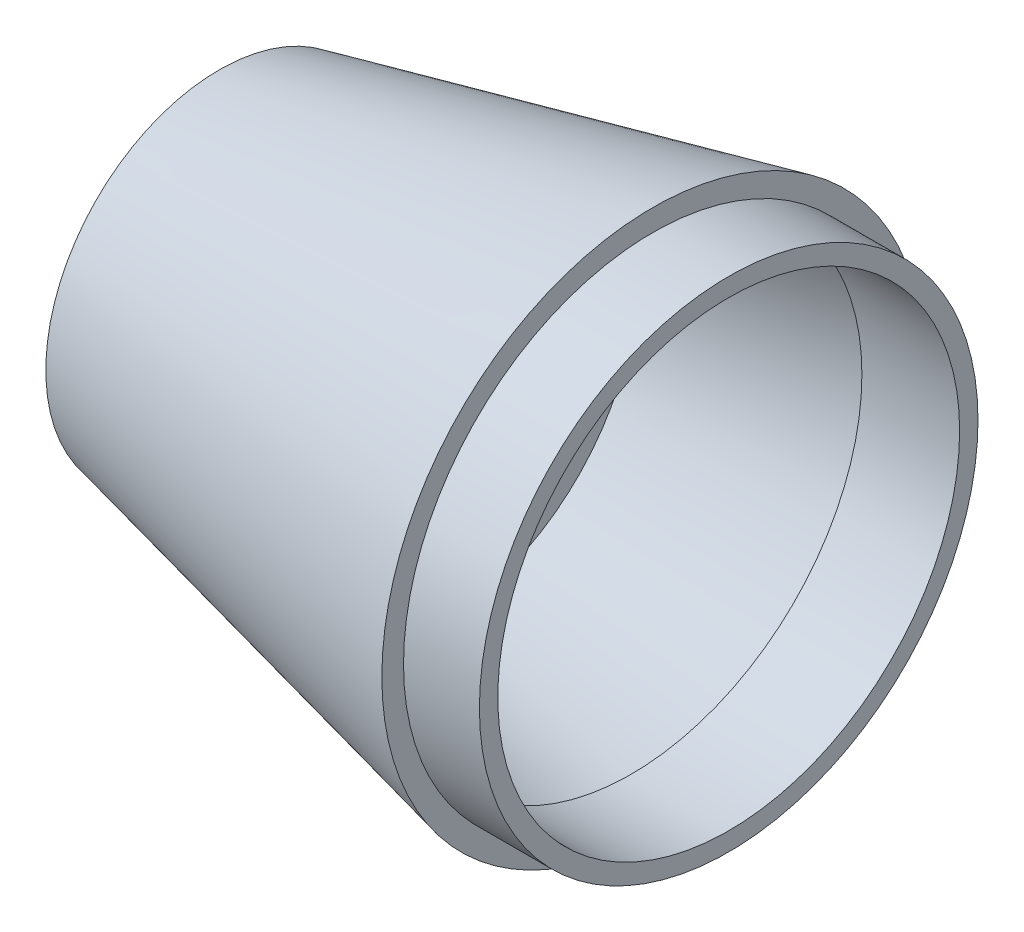
SolidWorks part; units mm, degrees
ref_plane "Front Plane" through (0, 0, 0) normal (0, 0, 1) x (1, 0, 0)
ref_plane "Top Plane" through (0, 0, 0) normal (0, 1, 0) x (1, 0, 0)
ref_plane "Right Plane" through (0, 0, 0) normal (1, 0, 0) x (0, 0, -1)
sketch "Sketch1" plane through (0, 0, 0) normal (0, 0, 1) x (1, 0, 0)
  line L0 (-12.065, 10.16) -> (-12.065, 8.89)
  line L1 (44.7264, 0) -> (-69.8413, 0) construction
  line L2 (13.335, 15.875) -> (13.335, 14.605)
  line L3 (-12.065, 0) -> (14.2126, 0) construction
  line L4 (-0.8483, 12.6838) -> (-0.8483, 0)
  line L5 (13.335, 15.875) -> (-12.065, 10.16)
  line L6 (-12.065, 8.89) -> (13.335, 14.605)
  line L7 (-0.8483, 0) -> (0.635, 0)
  line L8 (0.635, 0) -> (0.635, 13.0175)
  line L9 (0.635, 13.0175) -> (-0.8483, 12.6838)
  line L11 (17.749, 13.5286) -> (12.0566, 13.5286)
  line L12 (12.0566, 13.5286) -> (12.0566, 14.3174)
  line L13 (12.0566, 14.3174) -> (13.335, 14.605)
  line L14 (13.335, 14.605) -> (17.7812, 14.605)
  line L15 (17.7812, 13.5286) -> (17.749, 13.5286)
  line L16 (17.7812, 14.605) -> (17.7812, 13.5286)
  point P10 (17.749, 13.0927)
  dimension "D1" = 25.4
  dimension "D2" = 1.27
  dimension "D3" = 10.16
  dimension "D4" = 15.875
  dimension "D5" = 1.27
revolve "Revolve4" add sketch "Sketch1" angle 360 about L1
